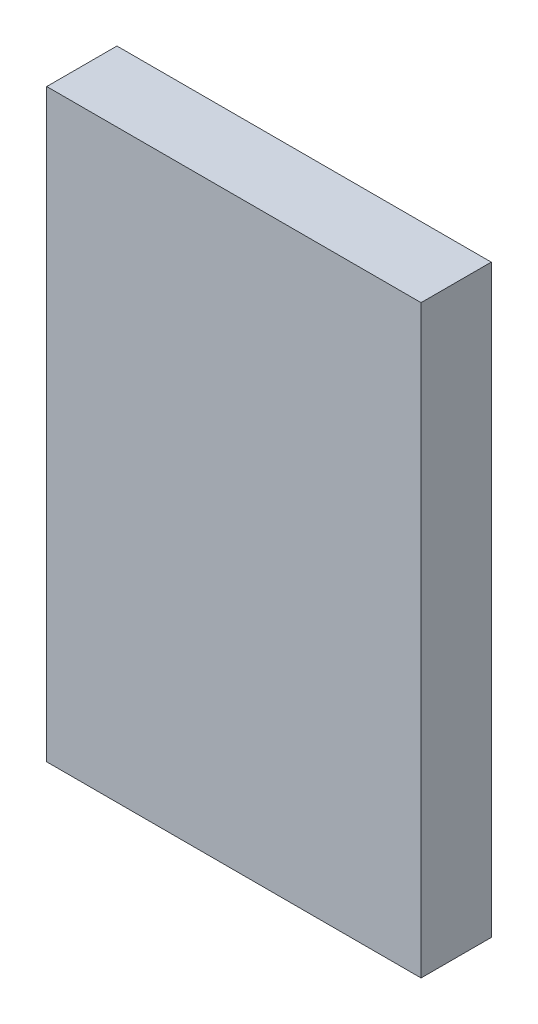
SolidWorks part; units mm, degrees
ref_plane "Front Plane" through (0, 0, 0) normal (0, 0, 1) x (1, 0, 0)
ref_plane "Top Plane" through (0, 0, 0) normal (0, 1, 0) x (1, 0, 0)
ref_plane "Right Plane" through (0, 0, 0) normal (1, 0, 0) x (0, 0, -1)
sketch "Sketch1" plane through (0, 0, 0) normal (0, 0, 1) x (1, 0, 0)
  line L0 (15.24, -23.8125) -> (15.24, 20.193)
  line L2 (-15.24, 23.8125) -> (-15.24, -23.8125)
  line L3 (-15.24, -23.8125) -> (15.24, -23.8125)
  line L7 (-15.24, 23.8125) -> (15.24, 23.8125)
  line L8 (15.24, 23.8125) -> (15.24, 20.193)
  point P3 (0, -23.8125)
  point P6 (-15.24, 0)
  dimension "D1" = 30.48
  dimension "D2" = 47.625
extrude "Boss-Extrude1" add sketch "Sketch1" along normal blind 5.715
